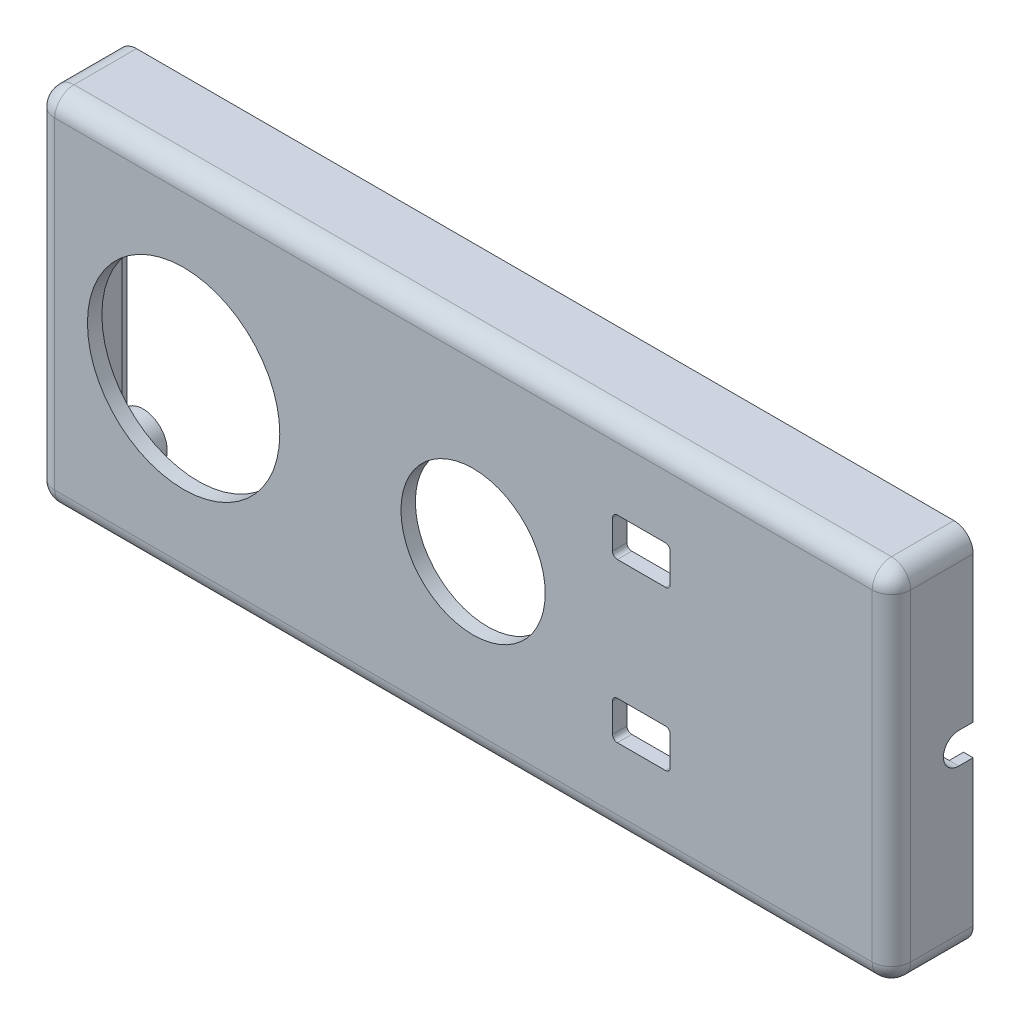
SolidWorks part; units mm, degrees
ref_plane "前视基准面" through (0, 0, 0) normal (0, 0, 1) x (1, 0, 0)
ref_plane "上视基准面" through (0, 0, 0) normal (0, 1, 0) x (1, 0, 0)
ref_plane "右视基准面" through (0, 0, 0) normal (1, 0, 0) x (0, 0, -1)
sketch "草图1" plane through (0, 0, 0) normal (0, 0, 1) x (1, 0, 0)
  line L1 (-44.5, 18.75) -> (44.5, 18.75)
  line L2 (-44.5, 18.75) -> (-44.5, -18.75)
  line L3 (-44.5, -18.75) -> (44.5, -18.75)
  line L4 (44.5, 18.75) -> (44.5, -18.75)
  line L5 (-44.5, 18.75) -> (44.5, -18.75) construction
  line L6 (-44.5, -18.75) -> (44.5, 18.75) construction
  point P0 (0, 0)
  dimension "D1" = 89
  dimension "D2" = 37.5
extrude "凸台-拉伸1" add sketch "草图1" along normal blind 8.5
sketch "草图2" plane through (0, 0, 0) normal (0, 0, -1) x (-1, 0, 0)
  line L0 (-44.5, 18.75) -> (44.5, 18.75) construction
  line L1 (-42.5, 16.75) -> (42.5, 16.75)
  line L2 (-42.5, 16.75) -> (-42.5, -16.75)
  line L3 (-42.5, -16.75) -> (42.5, -16.75)
  line L4 (42.5, 16.75) -> (42.5, -16.75)
  line L5 (44.5, -18.75) -> (-44.5, -18.75) construction
  line L6 (-44.5, -18.75) -> (-44.5, 18.75) construction
  line L7 (44.5, 18.75) -> (44.5, -18.75) construction
  dimension "D1" = 2
  dimension "D2" = 2
  dimension "D3" = 2
  dimension "D4" = 2
extrude "切除-拉伸1" cut sketch "草图2" against normal blind 7
sketch "草图3" plane through (44.5, 0, 0) normal (1, 0, 0) x (0, 0, -1)
  line L0 (0, -18.75) -> (0, 18.75) construction
  line L1 (0, 1.6) -> (0, -1.6)
  line L2 (0, 1.6) -> (-1.5, 1.6)
  line L3 (0, -1.6) -> (-1.5, -1.6)
  arc A1 (-1.5, 1.6) -> (-1.5, -1.6) centre (-1.5, 0) ccw
  dimension "D1" = 1.5
  dimension "D3" = 1.6
  dimension "D2" = 1.5
extrude "切除-拉伸3" cut sketch "草图3" against normal blind 4
fillet "圆角1" radius 2 12 edges at (0, -18.75, 8.5) (-44.5, 0, 8.5) (0, 18.75, 8.5) (44.5, 0, 8.5) (-44.5, 18.75, 4.25) (-44.5, -18.75, 4.25) (44.5, -18.75, 4.25) (44.5, 18.75, 4.25) (42.5, -16.75, 3.5) (42.5, 16.75, 3.5) (-42.5, 16.75, 3.5) (-42.5, -16.75, 3.5)
sketch "草图9" plane through (0, 0, 0) normal (0, 0, -1) x (-1, 0, 0)
  line L0 (-43.5, 15.75) -> (-43.5, 1.6)
  line L5 (-42.5, 1.6) -> (-44.5, 1.6) construction
  line L10 (42.5, -14.75) -> (42.5, 14.75) construction
  line L15 (-43.5, 1.6) -> (-42.5, 1.6)
  line L20 (40.5, 16.75) -> (-40.5, 16.75) construction
  line L21 (-40.5, -16.75) -> (40.5, -16.75) construction
  line L26 (-41.5, 17.75) -> (41.5, 17.75)
  line L28 (-41.5, -17.75) -> (41.5, -17.75)
  line L29 (43.5, 15.75) -> (43.5, -15.75)
  line L35 (-40.5, 16.75) -> (40.5, 16.75)
  line L37 (-40.5, -16.75) -> (40.5, -16.75)
  line L38 (42.5, 14.75) -> (42.5, -14.75)
  line L46 (-42.5, 1.6) -> (-42.5, 14.75)
  line L47 (-43.5, -15.75) -> (-43.5, -1.6)
  line L48 (-42.5, -1.6) -> (-44.5, -1.6) construction
  line L49 (-43.5, -1.6) -> (-42.5, -1.6)
  line L50 (-42.5, -1.6) -> (-42.5, -14.75)
  arc A0 (-43.5, -15.75) -> (-41.5, -17.75) centre (-41.5, -15.75) ccw
  arc A1 (-41.5, 17.75) -> (-43.5, 15.75) centre (-41.5, 15.75) ccw
  arc A2 (41.5, 17.75) -> (43.5, 15.75) centre (41.5, 15.75) cw
  arc A3 (41.5, -17.75) -> (43.5, -15.75) centre (41.5, -15.75) ccw
  arc A4 (-40.5, 16.75) -> (-42.5, 14.75) centre (-40.5, 14.75) ccw
  arc A5 (-42.5, -14.75) -> (-40.5, -16.75) centre (-40.5, -14.75) ccw
  arc A6 (40.5, 16.75) -> (42.5, 14.75) centre (40.5, 14.75) cw
  arc A7 (40.5, -16.75) -> (42.5, -14.75) centre (40.5, -14.75) ccw
  point P64 (42.5, -16.75)
  dimension "D20" = 2
  dimension "D21" = 2
  dimension "D22" = 2
  dimension "D23" = 2
  dimension "D26" = 2
  dimension "D27" = 2
  dimension "D28" = 2
  dimension "D29" = 2
  dimension "D17" = 1
  dimension "D18" = 1
  dimension "D19" = 1
  dimension "D25" = 1
extrude "凸台-拉伸2" add sketch "草图9" along normal blind 1
sketch "草图10" plane through (0, 0, 7) normal (0, 0, -1) x (-1, 0, 0)
  line L0 (42.5, -14.75) -> (42.5, 14.75) construction
  line L1 (-40.5, -16.75) -> (40.5, -16.75) construction
  line L2 (40.5, 16.75) -> (-40.5, 16.75) construction
  line L5 (-42.5, 14.75) -> (-42.5, -14.75) construction
  line L6 (40.5, -16.75) -> (-40.5, -16.75) construction
  circle A0 centre (39.3, -13.35) radius 2.5
  circle A1 centre (39.3, 13.35) radius 2.5
  circle A2 centre (-34.5, 13.35) radius 2.5
  circle A3 centre (-34.5, -13.35) radius 2.5
  dimension "D1" = 5
  dimension "D2" = 3.2
  dimension "D3" = 3.4
  dimension "D4" = 3.2
  dimension "D5" = 5
  dimension "D6" = 3.4
  dimension "D7" = 5
  dimension "D8" = 3.4
  dimension "D9" = 8
  dimension "D10" = 5
  dimension "D11" = 3.4
  dimension "D12" = 8
extrude "凸台-拉伸3" add sketch "草图10" along normal blind 4.5
sketch "草图11" plane through (0, 0, 2.5) normal (0, 0, -1) x (-1, 0, 0)
  circle A0 centre (-34.5, 13.35) radius 0.79
  circle A1 centre (-34.5, -13.35) radius 0.79
  circle A2 centre (39.3, 13.35) radius 0.79
  circle A3 centre (39.3, -13.35) radius 0.79
  dimension "D1" = 1.58
  dimension "D2" = 1.58
  dimension "D3" = 1.58
  dimension "D4" = 1.58
extrude "切除-拉伸9" cut sketch "草图11" against normal blind 3
sketch "草图8" plane through (0, 0, 7) normal (0, 0, -1) x (-1, 0, 0)
  line L1 (-40.5, -16.75) -> (40.5, -16.75) construction
  line L2 (42.5, -14.75) -> (42.5, 14.75) construction
  circle A0 centre (-1, -0.55) radius 7.5
  dimension "D1" = 15
  dimension "D2" = 16.2
  dimension "D3" = 43.5
extrude "切除-拉伸8" cut sketch "草图8" against normal blind 3
sketch "草图7" plane through (0, 0, 7) normal (0, 0, -1) x (-1, 0, 0)
  line L0 (40.5, -16.75) -> (-40.5, -16.75) construction
  line L1 (42.5, -14.75) -> (42.5, 14.75) construction
  circle A0 centre (29.1, 0) radius 10
  dimension "D1" = 20
  dimension "D2" = 13.4
  dimension "D3" = 16.75
extrude "切除-拉伸7" cut sketch "草图7" against normal blind 3
sketch "草图13" plane through (0, 0, -1) normal (0, 0, -1) x (-1, 0, 0)
  line L0 (-44.5, 1.6) -> (-44.5, 16.75) construction
  line L1 (-41.5, 17.75) -> (41.5, 17.75)
  line L2 (-43.5, 15.75) -> (-43.5, -15.75)
  line L3 (-41.5, -17.75) -> (41.5, -17.75)
  line L4 (43.5, 15.75) -> (43.5, -15.75)
  line L5 (-42.5, 18.75) -> (42.5, 18.75) construction
  line L6 (44.5, 16.75) -> (44.5, -16.75) construction
  line L7 (42.5, -18.75) -> (-42.5, -18.75) construction
  arc A0 (-41.5, 17.75) -> (-43.5, 15.75) centre (-41.5, 15.75) ccw
  arc A1 (-43.5, -15.75) -> (-41.5, -17.75) centre (-41.5, -15.75) ccw
  arc A2 (41.5, -17.75) -> (43.5, -15.75) centre (41.5, -15.75) ccw
  arc A3 (41.5, 17.75) -> (43.5, 15.75) centre (41.5, 15.75) cw
  dimension "D5" = 2
  dimension "D6" = 2
  dimension "D7" = 2
  dimension "D8" = 2
  dimension "D1" = 1
  dimension "D2" = 1
  dimension "D3" = 1
  dimension "D4" = 1
extrude "切除-拉伸10" cut sketch "草图13" against normal blind 2.5
sketch "草图14" plane through (0, 0, 7) normal (0, 0, -1) x (-1, 0, 0)
  line L0 (40.5, -16.75) -> (-40.5, -16.75) construction
  line L1 (-21, -6.25) -> (-16, -6.25)
  line L2 (-21.5, -6.75) -> (-21.5, -9.75)
  line L3 (-21, -10.25) -> (-16, -10.25)
  line L4 (-15.5, -6.75) -> (-15.5, -9.75)
  line L5 (-21, 10.25) -> (-16, 10.25)
  line L6 (-21.5, 9.75) -> (-21.5, 6.75)
  line L7 (-21, 6.25) -> (-16, 6.25)
  line L8 (-15.5, 9.75) -> (-15.5, 6.75)
  line L9 (-42.5, 14.75) -> (-42.5, -14.75) construction
  line L10 (-40.5, 16.75) -> (40.5, 16.75) construction
  arc A0 (-21, 10.25) -> (-21.5, 9.75) centre (-21, 9.75) ccw
  arc A1 (-16, 10.25) -> (-15.5, 9.75) centre (-16, 9.75) cw
  arc A2 (-21.5, 6.75) -> (-21, 6.25) centre (-21, 6.75) ccw
  arc A3 (-16, 6.25) -> (-15.5, 6.75) centre (-16, 6.75) ccw
  arc A4 (-21, -6.25) -> (-21.5, -6.75) centre (-21, -6.75) ccw
  arc A5 (-16, -6.25) -> (-15.5, -6.75) centre (-16, -6.75) cw
  arc A6 (-16, -10.25) -> (-15.5, -9.75) centre (-16, -9.75) ccw
  arc A7 (-21.5, -9.75) -> (-21, -10.25) centre (-21, -9.75) ccw
  point P16 (-21.5, 10.25)
  point P19 (-15.5, 10.25)
  point P22 (-21.5, 6.25)
  point P27 (-21.5, -6.25)
  point P32 (-15.5, -10.25)
  point P35 (-21.5, -10.25)
  dimension "D9" = 0.5
  dimension "D10" = 0.5
  dimension "D11" = 0.5
  dimension "D12" = 0.5
  dimension "D13" = 0.5
  dimension "D14" = 0.5
  dimension "D15" = 0.5
  dimension "D16" = 0.5
  dimension "D1" = 6
  dimension "D2" = 4
  dimension "D3" = 6.5
  dimension "D4" = 21
  dimension "D5" = 6
  dimension "D6" = 4
  dimension "D7" = 21
  dimension "D8" = 6.5
extrude "切除-拉伸11" cut sketch "草图14" against normal blind 10
